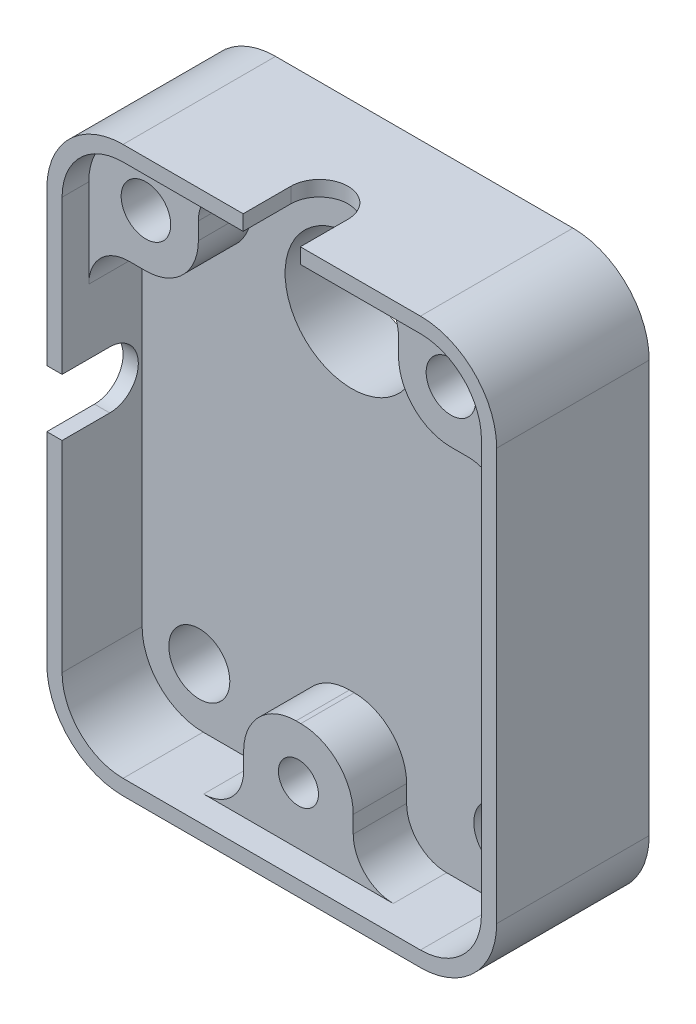
SolidWorks part; units mm, degrees
ref_plane "Front" through (0, 0, 0) normal (0, 0, 1) x (1, 0, 0)
ref_plane "Top" through (0, 0, 0) normal (0, 1, 0) x (1, 0, 0)
ref_plane "Right" through (0, 0, 0) normal (1, 0, 0) x (0, 0, -1)
sketch "Sketch1" plane through (0, 0, 0) normal (0, 0, 1) x (1, 0, 0)
  line L8 (11.8, 14.8) -> (-11.8, 14.8)
  line L9 (-11.8, 14.8) -> (-11.8, -14.8)
  line L10 (-11.8, -14.8) -> (11.8, -14.8)
  line L11 (11.8, -14.8) -> (11.8, 14.8)
  line L12 (11.8, 14.8) -> (-11.8, 14.8)
  line L13 (-11.8, 14.8) -> (-11.8, -14.8)
  line L14 (-11.8, -14.8) -> (11.8, -14.8)
  line L15 (11.8, -14.8) -> (11.8, 14.8)
  dimension "D1" = 0
extrude "Basic" add sketch "Sketch1" along normal blind 8
sketch "Sketch2" plane through (0, 0, 8) normal (0, 0, 1) x (1, 0, 0)
  circle A1 centre (0, 9) radius 3.5
  circle A2 centre (0, 9) radius 3.5
  dimension "D1" = 0
extrude "Ø7.0 Hole (Rotating Magnet)" cut sketch "Sketch2" against normal through all
sketch "Sketch4" plane through (0, 0, 8) normal (0, 0, 1) x (1, 0, 0)
  circle A2 centre (8, -11) radius 1.6
  circle A4 centre (-8, -11) radius 1.6
  circle A6 centre (8, 11) radius 1.3
  circle A8 centre (-8, 11) radius 1.3
  dimension "D3" = 2.6
  dimension "D1" = 3.2
extrude "Mounting holes  Ø2.05 & Ø2.5" cut sketch "Sketch4" against normal through all
sketch "Sketch5" plane through (0, 0, 8) normal (0, 0, 1) x (1, 0, 0)
  circle A2 centre (8, 0) radius 1.55
  circle A4 centre (-8, 0) radius 1.55
  dimension "D3" = 3.1
extrude "Ø3.1 Nipples" [suppressed] cut sketch "Sketch5" against normal through all
fillet "R4: Basic" radius 4 4 edges at (-11.8, -14.8, 4) (11.8, -14.8, 4) (11.8, 14.8, 4) (-11.8, 14.8, 4)
sketch "Sketch6" plane through (0, 0, 8) normal (0, 0, 1) x (1, 0, 0)
  line L15 (11, -10.8) -> (11, 10.8)
  line L16 (7.8, 14) -> (-7.8, 14)
  line L17 (-11, 10.8) -> (-11, -10.8)
  line L18 (-7.8, -14) -> (7.8, -14)
  line L19 (11, -10.8) -> (11, 10.8)
  line L20 (7.8, 14) -> (-7.8, 14)
  line L21 (-11, 10.8) -> (-11, -10.8)
  line L22 (-7.8, -14) -> (7.8, -14)
  arc A4 (-11, -10.8) -> (-7.8, -14) centre (-7.8, -10.8) ccw
  arc A5 (-11, -10.8) -> (-7.8, -14) centre (-7.8, -10.8) ccw
  arc A6 (7.8, -14) -> (11, -10.8) centre (7.8, -10.8) ccw
  arc A7 (7.8, -14) -> (11, -10.8) centre (7.8, -10.8) ccw
  arc A8 (11, 10.8) -> (7.8, 14) centre (7.8, 10.8) ccw
  arc A9 (11, 10.8) -> (7.8, 14) centre (7.8, 10.8) ccw
  arc A10 (-7.8, 14) -> (-11, 10.8) centre (-7.8, 10.8) ccw
  arc A11 (-7.8, 14) -> (-11, 10.8) centre (-7.8, 10.8) ccw
  dimension "D1" = 0.8
extrude "PCB level" cut sketch "Sketch6" against normal blind 1.4
sketch "Sketch9" plane through (0, 0, 8) normal (0, 0, 1) x (1, 0, 0)
  line L0 (-11, 8.25) -> (-5.25, 8.25)
  line L1 (-5.25, 8.25) -> (-5.25, 14)
  line L2 (5.25, 14) -> (5.25, 8.25)
  line L3 (5.25, 8.25) -> (11, 8.25)
  line L4 (7.8, 14) -> (-7.8, 14)
  line L5 (-11, 10.8) -> (-11, -10.8)
  line L6 (-7.8, -14) -> (7.8, -14)
  line L7 (11, -10.8) -> (11, 10.8)
  line L8 (5.25, 14) -> (-5.25, 14)
  line L9 (-11, 8.25) -> (-11, -10.8)
  line L10 (-7.8, -14) -> (-2.875, -14)
  line L11 (11, -10.8) -> (11, 8.25)
  line L12 (7.8, 14.8) -> (-7.8, 14.8) construction
  line L13 (11.8, -10.8) -> (11.8, 10.8) construction
  line L14 (-11.8, 10.8) -> (-11.8, -10.8) construction
  line L19 (-7.8, -14.8) -> (7.8, -14.8) construction
  line L20 (-2.875, -14) -> (-2.875, -8.25)
  line L21 (-2.875, -8.25) -> (2.875, -8.25)
  line L22 (2.875, -8.25) -> (2.875, -14)
  line L23 (2.875, -14) -> (7.8, -14)
  arc A0 (-11, -10.8) -> (-7.8, -14) centre (-7.8, -10.8) ccw construction
  arc A1 (-11, -10.8) -> (-7.8, -14) centre (-7.8, -10.8) ccw
  arc A2 (7.8, -14) -> (11, -10.8) centre (7.8, -10.8) ccw construction
  arc A3 (7.8, -14) -> (11, -10.8) centre (7.8, -10.8) ccw
  arc A4 (11, 10.8) -> (7.8, 14) centre (7.8, 10.8) ccw
  arc A5 (-7.8, 14) -> (-11, 10.8) centre (-7.8, 10.8) ccw
  arc A6 (-11, -10.8) -> (-7.8, -14) centre (-7.8, -10.8) ccw
  arc A7 (7.8, -14) -> (11, -10.8) centre (7.8, -10.8) ccw
  point P22 (11.8, 14.8)
  point P25 (-11.8, 14.8)
  point P26 (0, -8.25)
  point P34 (-11.8, -14.8)
  point P35 (11.8, -14.8)
  dimension "D2" = 6.55
  dimension "D3" = 6.55
  dimension "D1" = 0
extrude "PCB Clearance" cut sketch "Sketch9" against normal blind 4.2
fillet "R2.1: PCB Clearance" radius 2.1 6 edges at (11, 8.25, 5.2) (5.25, 14, 5.2) (-11, 8.25, 5.2) (-5.25, 14, 5.2) (2.875, -14, 5.2) (-2.875, -14, 5.2)
fillet "R2.75: PCB Clearance" radius 2.75 4 edges at (5.25, 8.25, 5.2) (-5.25, 8.25, 5.2) (-2.875, -8.25, 5.2) (2.875, -8.25, 5.2)
sketch "Sketch11" plane through (0, 14.8, 0) normal (0, 1, 0) x (1, 0, 0)
  line L0 (-1.5, -8) -> (-1.5, -5.5)
  line L1 (7.8, -8) -> (-7.8, -8) construction
  line L2 (-1.5, -8) -> (1.5, -8)
  line L3 (1.5, -8) -> (1.5, -5.5)
  arc A0 (-1.5, -5.5) -> (1.5, -5.5) centre (0, -5.5) cw
  dimension "D1" = 3
  dimension "D2" = 2.5
extrude "Cut-Out (1)" cut sketch "Sketch11" against normal up to surface (0.8 mm away) up to face at (0, 14, 6.25)
sketch "Sketch12" plane through (-11.8, 0, 0) normal (-1, 0, 0) x (0, 0, 1)
  line L0 (8, -0.25) -> (5.5, -0.25)
  line L1 (8, 10.8) -> (8, -10.8) construction
  line L2 (8, -0.25) -> (8, 2.75)
  line L3 (8, 2.75) -> (5.5, 2.75)
  arc A0 (5.5, -0.25) -> (5.5, 2.75) centre (5.5, 1.25) cw
  dimension "D1" = 3
  dimension "D2" = 2.5
  dimension "D3" = 1.25
extrude "Cut-Out Reset Switch" cut sketch "Sketch12" against normal up to surface (0.8 mm away) up to face at (-11, 2.05, 6.1333)
sketch "Sketch13" plane through (0, 0, 6.6) normal (0, 0, 1) x (1, 0, 0)
  circle A0 centre (0, -11) radius 1.05
  dimension "D2" = 2.1
  dimension "D1" = 11
extrude "Ø2.05 PCB Mounting Hole for M2.5" cut sketch "Sketch13" against normal through all
sketch "Sketch15" plane through (0, 4.25, -7.6) normal (0, -1, 0) x (1, 0, 0)
  line L0 (-15, 4.4) -> (15, 4.4) construction
  line L1 (-15, 4.4) -> (15, 4.4) construction
  line L16 (5.8, 6.65) -> (3.8, 6.65)
  line L17 (5.8, 7.9) -> (5.8, 6.65)
  line L18 (9.8, 7.9) -> (5.8, 7.9)
  line L19 (9.8, 6.9) -> (9.8, 7.9)
  line L20 (11.8, 6.9) -> (9.8, 6.9)
  line L21 (11.8, 4.4) -> (11.8, 6.9)
  line L22 (-11.8, 4.4) -> (11.8, 4.4)
  line L23 (-11.8, 6.9) -> (-11.8, 4.4)
  line L24 (-9.8, 6.9) -> (-11.8, 6.9)
  line L25 (-9.8, 7.9) -> (-9.8, 6.9)
  line L26 (-5.8, 7.9) -> (-9.8, 7.9)
  line L27 (-5.8, 6.65) -> (-5.8, 7.9)
  line L28 (-3.8, 6.65) -> (-5.8, 6.65)
  line L29 (-3.8, 5.5) -> (-3.8, 6.65)
  line L30 (3.8, 5.5) -> (-3.8, 5.5)
  line L31 (3.8, 6.65) -> (3.8, 5.5)
  line L32 (5.8, 6.65) -> (3.8, 6.65)
  line L33 (5.8, 7.9) -> (5.8, 6.65)
  line L34 (9.8, 7.9) -> (5.8, 7.9)
  line L35 (9.8, 6.9) -> (9.8, 7.9)
  line L36 (11.8, 6.9) -> (9.8, 6.9)
  line L37 (11.8, 4.4) -> (11.8, 6.9)
  line L38 (-11.8, 4.4) -> (11.8, 4.4)
  line L39 (-11.8, 6.9) -> (-11.8, 4.4)
  line L40 (-9.8, 6.9) -> (-11.8, 6.9)
  line L41 (-9.8, 7.9) -> (-9.8, 6.9)
  line L42 (-5.8, 7.9) -> (-9.8, 7.9)
  line L43 (-5.8, 6.65) -> (-5.8, 7.9)
  line L44 (-3.8, 6.65) -> (-5.8, 6.65)
  line L45 (-3.8, 5.5) -> (-3.8, 6.65)
  line L46 (3.8, 5.5) -> (-3.8, 5.5)
  line L47 (3.8, 6.65) -> (3.8, 5.5)
  dimension "D1" = 0
revolve "Filament Transit Clearance" [suppressed] cut sketch "Sketch15" angle 360 about L1
